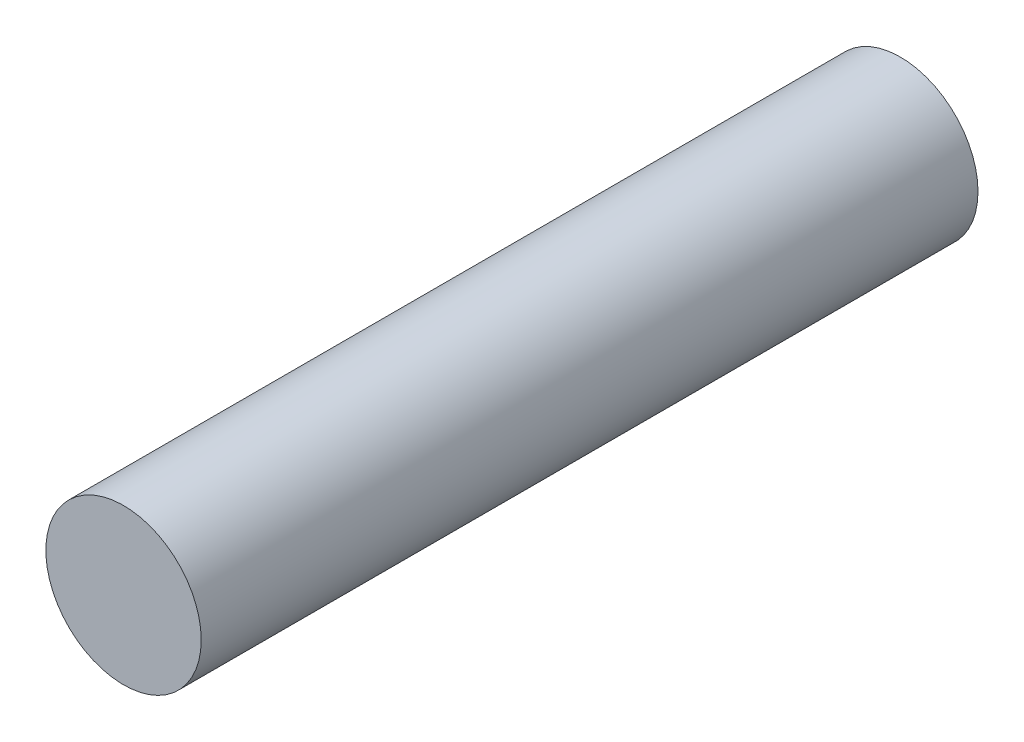
SolidWorks part; units mm, degrees
ref_plane "Front Plane" through (0, 0, 0) normal (0, 0, 1) x (1, 0, 0)
ref_plane "Top Plane" through (0, 0, 0) normal (0, 1, 0) x (1, 0, 0)
ref_plane "Right Plane" through (0, 0, 0) normal (1, 0, 0) x (0, 0, -1)
sketch "Sketch1" plane through (0, 0, 0) normal (0, 0, 1) x (1, 0, 0)
  circle A0 centre (0, 0) radius 1
  dimension "D1" = 2
extrude "Boss-Extrude1" add sketch "Sketch1" along normal blind 10
